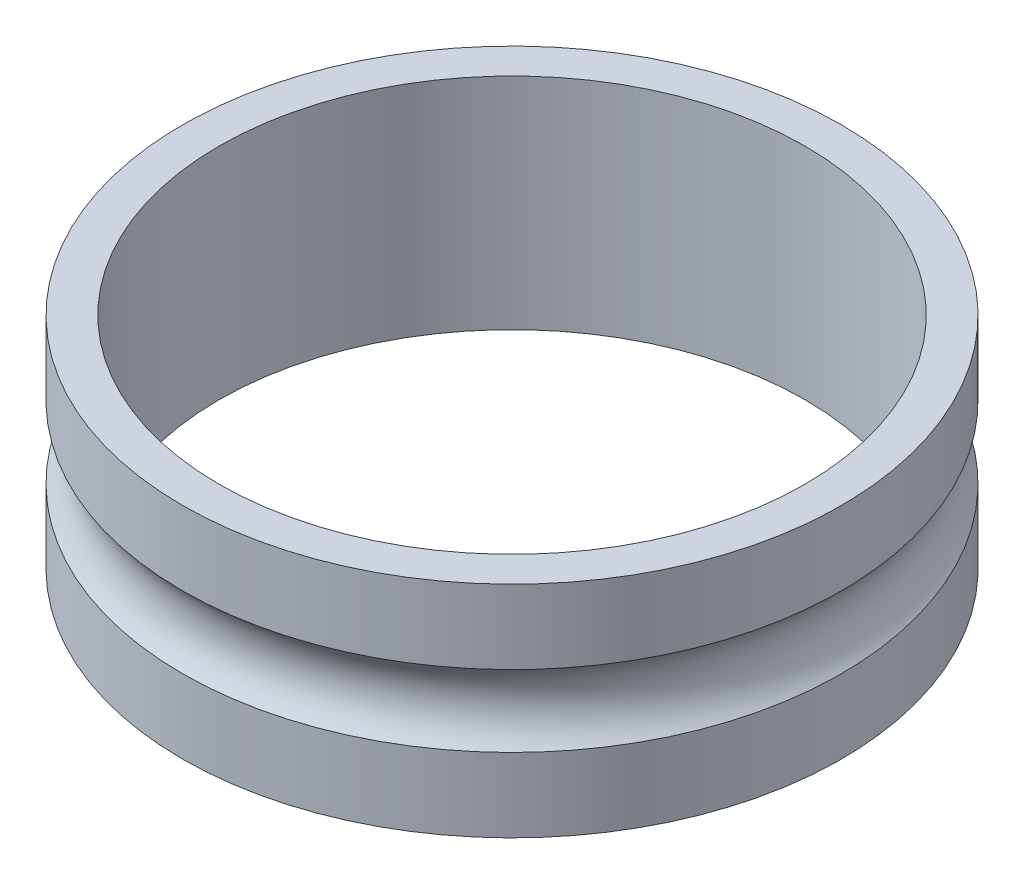
SolidWorks part; units mm, degrees
material "Chrome Stainless Steel"
ref_plane "Front Plane" through (0, 0, 0) normal (0, 0, 1) x (1, 0, 0)
ref_plane "Top Plane" through (0, 0, 0) normal (0, 1, 0) x (1, 0, 0)
ref_plane "Right Plane" through (0, 0, 0) normal (1, 0, 0) x (0, 0, -1)
sketch "Diameter Profile Sketch" plane through (0, 0, 0) normal (0, 1, 0) x (1, 0, 0)
  circle A0 centre (0, 0) radius 4
  circle A1 centre (0, 0) radius 4.5
  dimension "InnerDia" = 8
  dimension "Thickness" = 0.5
extrude "Diameter Profile" add sketch "Diameter Profile Sketch" along normal mid plane 3
sketch "Bearing Path Profile Sketch" plane through (0, 0, 0) normal (0, 0, 1) x (1, 0, 0)
  line L0 (0, 0) -> (5, 0) construction
  line L3 (0, 1.5) -> (0, -1.5) construction
  circle A0 centre (5, 0) radius 0.7
  dimension "BallDia" = 1.4
  dimension "YDim" = 0.5
  dimension "RefRadius" = 5
revolve "Bearing Path Profile" cut sketch "Bearing Path Profile Sketch" angle 360 about axis through (0, 1.5, 0) along (0, -1, 0)
